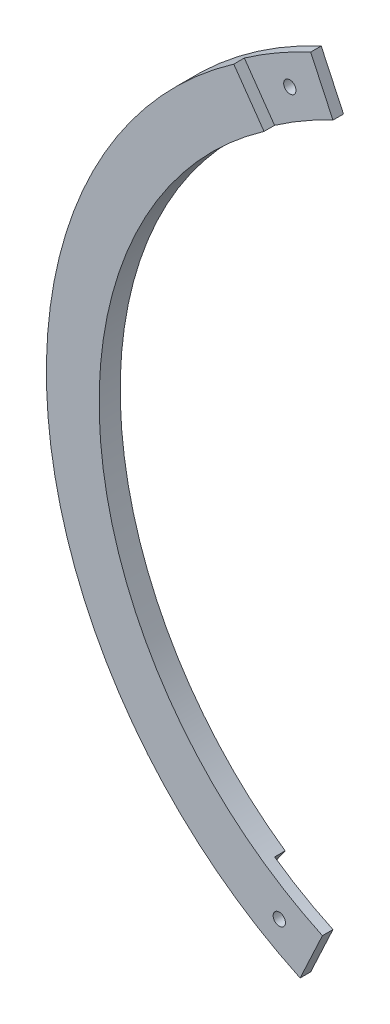
SolidWorks part; units mm, degrees
ref_plane "Plan de face" through (0, 0, 0) normal (0, 0, 1) x (1, 0, 0)
ref_plane "Plan de dessus" through (0, 0, 0) normal (0, 1, 0) x (1, 0, 0)
ref_plane "Plan de droite" through (0, 0, 0) normal (1, 0, 0) x (0, 0, -1)
sketch "Esquisse1" plane through (0, 0, 0) normal (0, 0, 1) x (1, 0, 0)
  line L1 (-120, 0) -> (-130, 0) construction
  line L6 (-130, 0) -> (0, 0) construction
  line L7 (-46.488, -99.6939) -> (-52.8273, -113.2885)
  line L8 (-46.488, 99.6939) -> (-52.8273, 113.2885)
  line L9 (0, 0) -> (-46.488, 99.6939) construction
  line L10 (0, 0) -> (-46.488, -99.6939) construction
  arc A0 (-52.8273, 113.2885) -> (-125, 0) centre (0, 0) ccw
  arc A1 (-46.488, 99.6939) -> (-46.488, -99.6939) centre (0, 0) ccw
  arc A2 (-125, 0) -> (-52.8273, -113.2885) centre (0, 0) ccw
  dimension "D5" = 125
  dimension "D6" = 110
  dimension "D1" = 120
  dimension "D3" = 10
  dimension "D7" = 65
  dimension "D8" = 65
extrude "Boss.-Extru.1" add sketch "Esquisse1" along normal blind 6
sketch "Esquisse3" plane through (0, 0, 6) normal (0, 0, 1) x (1, 0, 0)
  line L0 (-58.75, 101.758) -> (0, 0) construction
  line L1 (0, 0) -> (-58.75, -101.758) construction
  line L2 (-52.8273, 113.2885) -> (0, 0) construction
  circle A0 centre (-58.75, 101.758) radius 1.75
  circle A1 centre (-58.75, -101.758) radius 1.75
  dimension "D1" = 3.5
  dimension "D2" = 120
  dimension "D3" = 5
  dimension "D4" = 117.5
extrude "Enlèv. mat.-Extru.1" cut sketch "Esquisse3" against normal blind 10
sketch "Esquisse4" plane through (0, 0, 6) normal (0, 0, 1) x (1, 0, 0)
  line L0 (-71.6971, 102.394) -> (-63.0934, 90.1067)
  line L1 (-52.8273, 113.2885) -> (-46.488, 99.6939)
  line L2 (-46.488, 99.6939) -> (-52.8273, 113.2885) construction
  line L3 (-63.0934, 90.1067) -> (0, 0) construction
  arc A0 (-46.488, 99.6939) -> (-63.0934, 90.1067) centre (0, 0) ccw
  arc A1 (-71.6971, 102.394) -> (-52.8273, 113.2885) centre (0, 0) cw
  arc A2 (-52.8273, 113.2885) -> (-52.8273, -113.2885) centre (0, 0) ccw construction
  dimension "D1" = 10
extrude "Enlèv. mat.-Extru.2" cut sketch "Esquisse4" against normal blind 3
sketch "Esquisse6" plane through (0, 0, 0) normal (0, 0, -1) x (-1, 0, 0)
  line L0 (63.0934, -90.1067) -> (71.6971, -102.394)
  line L1 (46.488, -99.6939) -> (52.8273, -113.2885)
  line L2 (52.8273, -113.2885) -> (46.488, -99.6939) construction
  line L3 (63.0934, -90.1067) -> (0, 0) construction
  arc A0 (63.0934, -90.1067) -> (46.488, -99.6939) centre (0, 0) cw
  arc A1 (71.6971, -102.394) -> (52.8273, -113.2885) centre (0, 0) cw
  dimension "D1" = 10
extrude "Enlèv. mat.-Extru.3" cut sketch "Esquisse6" against normal blind 3
